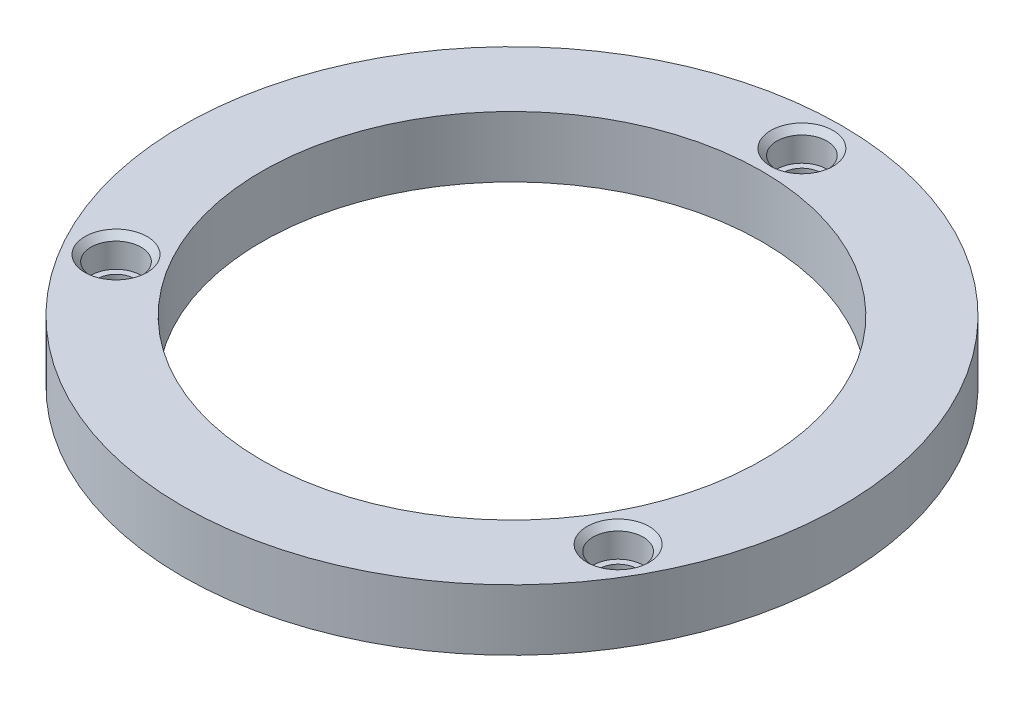
SolidWorks part; units mm, degrees
ref_plane "Front Plane" through (0, 0, 0) normal (0, 0, 1) x (1, 0, 0)
ref_plane "Top Plane" through (0, 0, 0) normal (0, 1, 0) x (1, 0, 0)
ref_plane "Right Plane" through (0, 0, 0) normal (1, 0, 0) x (0, 0, -1)
sketch "Sketch1" plane through (0, 0, 0) normal (0, 1, 0) x (1, 0, 0)
  circle A0 centre (0, 0) radius 41
  circle A1 centre (0, 0) radius 54
  dimension "D1" = 82
  dimension "D2" = 108
extrude "Boss-Extrude1" add sketch "Sketch1" along normal blind 10
sketch "Sketch2" plane through (0, 10, 0) normal (0, 1, 0) x (1, 0, 0)
  line L0 (0, -79.1209) -> (0, 94.5365) construction
  circle A0 centre (0, 0) radius 47.5 construction
  circle A1 centre (0, 47.5) radius 4.1
  circle A2 centre (41.1362, -23.75) radius 4.1
  circle A3 centre (-41.1362, -23.75) radius 4.1
  dimension "D1" = 95
  dimension "D2" = 8.2
  dimension "D3" = 3
extrude "Cut-Extrude1" cut sketch "Sketch2" against normal blind 5
sketch "Sketch3" plane through (0, 5, 0) normal (0, 1, 0) x (1, 0, 0)
  circle A0 centre (0, 47.5) radius 3.1
  circle A1 centre (0, 47.5) radius 4.1
  circle A2 centre (0, 47.5) radius 4.1 construction
  circle A3 centre (0, 0) radius 47.5 construction
  circle A4 centre (41.1362, -23.75) radius 3.1
  circle A5 centre (-41.1362, -23.75) radius 3.1
  dimension "D2" = 6.2
  dimension "D1" = 0
  dimension "D3" = 3
extrude "Cut-Extrude2" cut sketch "Sketch3" against normal up to next
chamfer "Chamfer1" distance 1 angle 45 3 edges at (-41.1362, 10, 27.85) (41.1362, 10, 27.85) (0, 10, -43.4)
